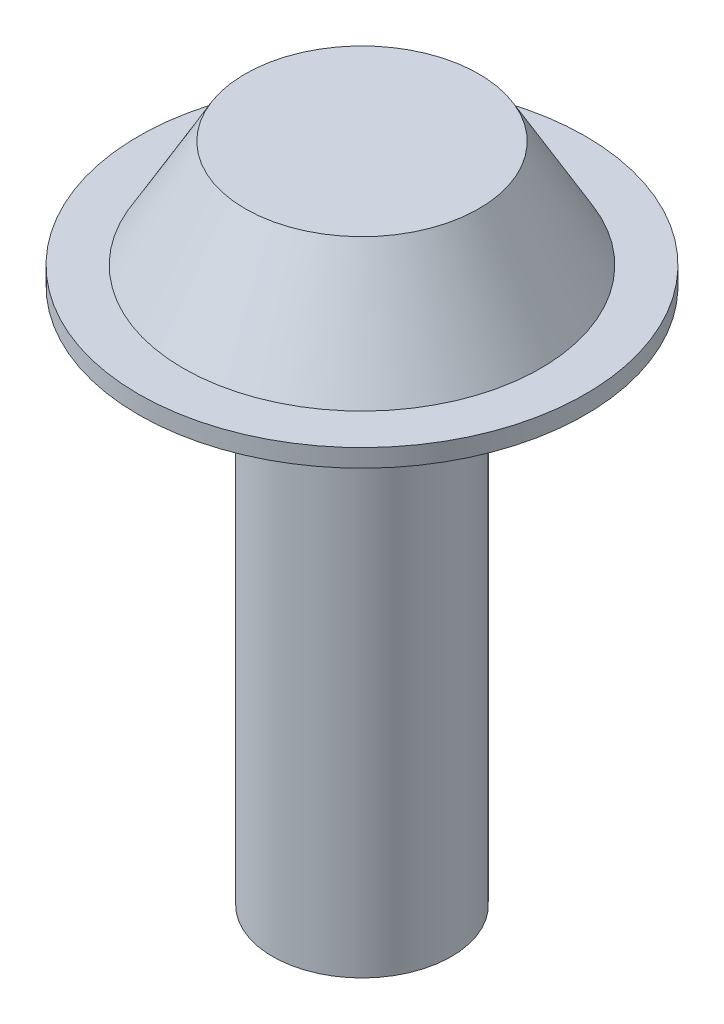
SolidWorks part; units mm, degrees
ref_plane "정면" through (0, 0, 0) normal (0, 0, 1) x (1, 0, 0)
ref_plane "윗면" through (0, 0, 0) normal (0, 1, 0) x (1, 0, 0)
ref_plane "우측면" through (0, 0, 0) normal (1, 0, 0) x (0, 0, -1)
sketch "스케치1" plane through (0, 0, 0) normal (0, 1, 0) x (1, 0, 0)
  circle A0 centre (0, 0) radius 2.5
  dimension "D1" = 5
extrude "보스-돌출1" add sketch "스케치1" along normal blind 0.2
sketch "스케치2" plane through (0, 0, 0) normal (0, -1, 0) x (1, 0, 0)
  circle A0 centre (0, 0) radius 1
  dimension "D1" = 2
extrude "보스-돌출2" add sketch "스케치2" along normal blind 6
sketch "스케치3" plane through (0, 0.2, 0) normal (0, 1, 0) x (1, 0, 0)
  circle A0 centre (0, 0) radius 2
  dimension "D1" = 4
extrude "보스-돌출3" add sketch "스케치3" along normal blind 1.2 draft 30
